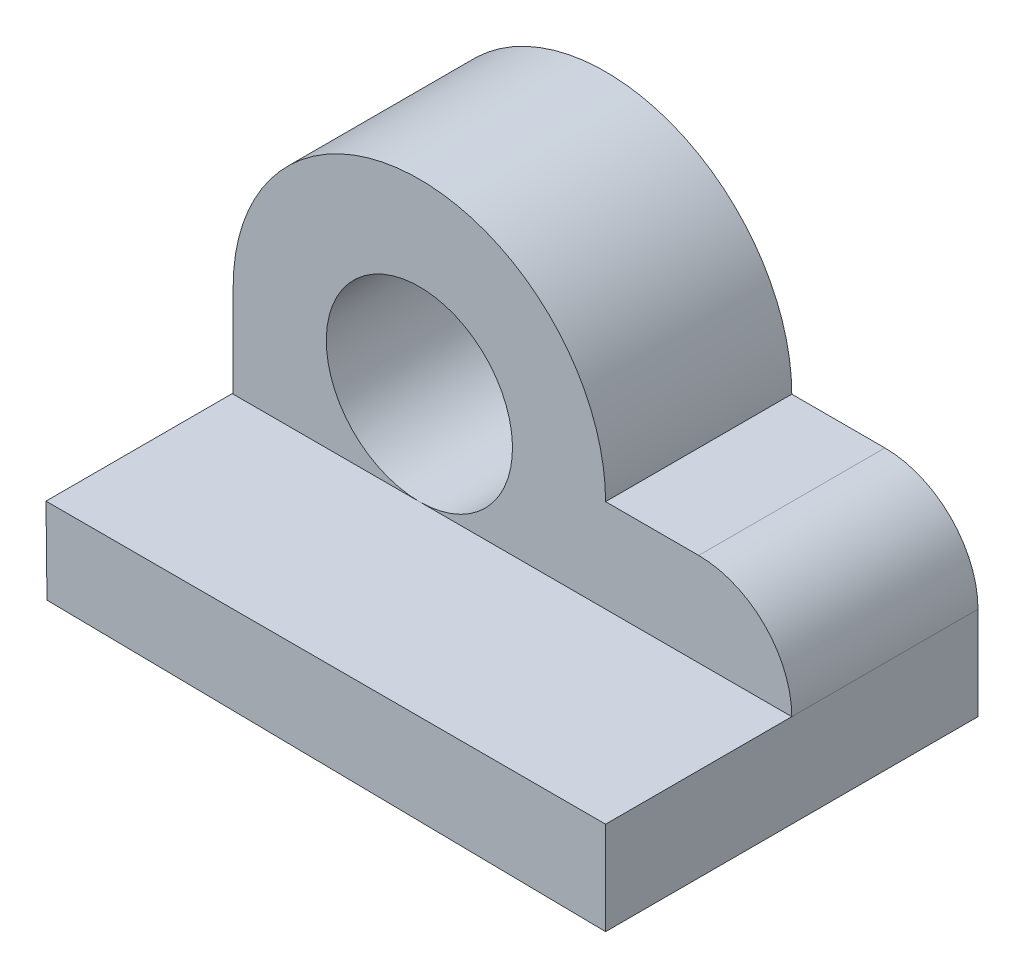
SolidWorks part; units mm, degrees
ref_plane "Front Plane" through (0, 0, 0) normal (0, 0, 1) x (1, 0, 0)
ref_plane "Top Plane" through (0, 0, 0) normal (0, 1, 0) x (1, 0, 0)
ref_plane "Right Plane" through (0, 0, 0) normal (1, 0, 0) x (0, 0, -1)
sketch "Sketch1" plane through (0, 0, 0) normal (0, 0, 1) x (1, 0, 0)
  line L1 (-20, 0) -> (-20, -10)
  line L4 (20, 0) -> (30, 0)
  line L5 (40, -10) -> (40, -20)
  line L8 (-20, -10) -> (-20, -19.1614)
  line L9 (-20, -19.1614) -> (40, -20)
  circle A0 centre (0, 0) radius 10
  arc A1 (20, 0) -> (-20, 0) centre (0, 0) ccw
  arc A2 (40, -10) -> (30, 0) centre (30, -10) ccw
  point P7 (0, -10)
  dimension "D1" = 10
extrude "Boss-Extrude1" add sketch "Sketch1" along normal blind 20
sketch "Sketch3" plane through (0, 0, 20) normal (0, 0, 1) x (1, 0, 0)
  line L0 (-20.1042, -10) -> (40, -10)
  line L1 (-20.1042, -10) -> (-20, -19.1614)
  line L2 (-20, -19.1614) -> (40, -20)
  line L3 (40, -20) -> (40, -10)
  point P3 (9.9479, -10)
extrude "Boss-Extrude2" add sketch "Sketch3" along normal blind 20
